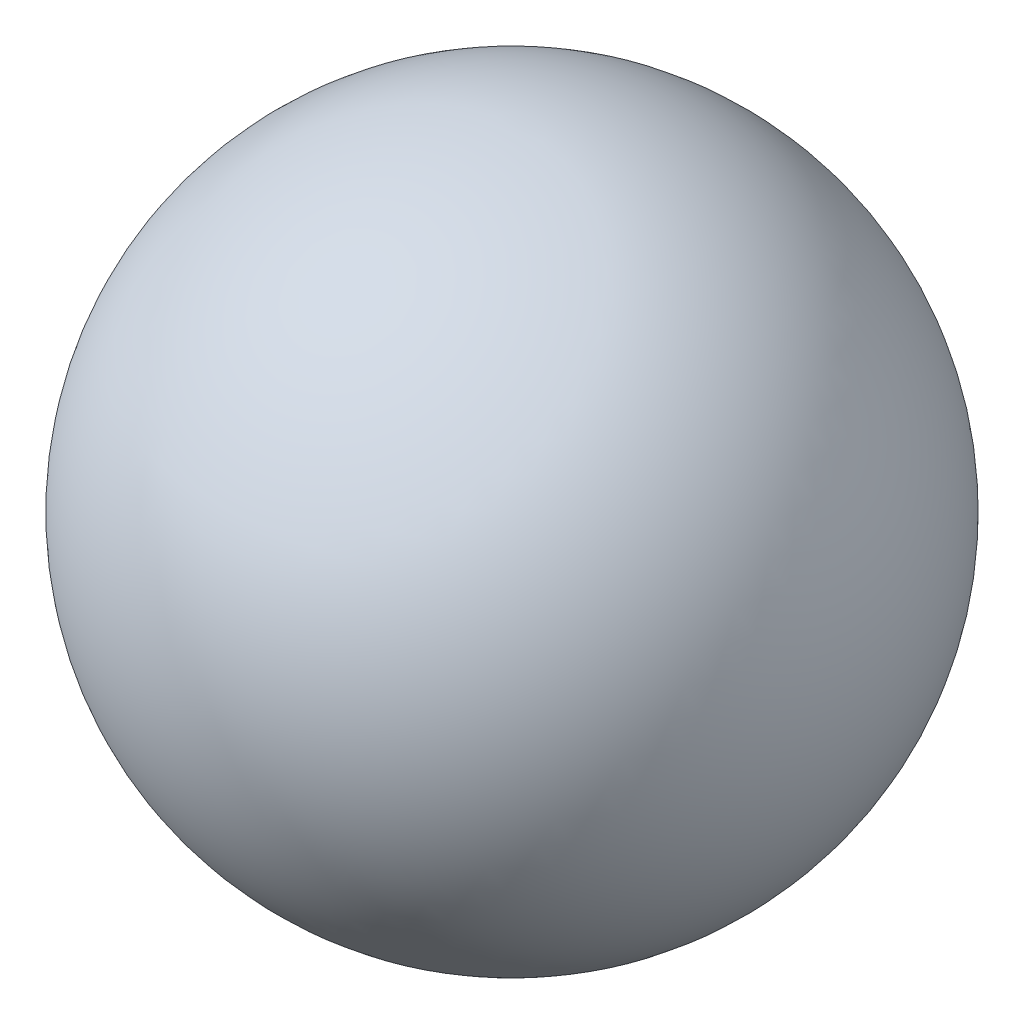
SolidWorks part; units mm, degrees
ref_plane "Front Plane" through (0, 0, 0) normal (0, 0, 1) x (1, 0, 0)
ref_plane "Top Plane" through (0, 0, 0) normal (0, 1, 0) x (1, 0, 0)
ref_plane "Right Plane" through (0, 0, 0) normal (1, 0, 0) x (0, 0, -1)
sketch "Sketch1" plane through (0, 0, 0) normal (0, 0, 1) x (1, 0, 0)
  line L0 (-1272.5132, -243.7844) -> (-1272.5132, 2156.2156)
  arc A0 (-1272.5132, -243.7844) -> (-1272.5132, 2156.2156) centre (-1272.5132, 956.2156) ccw
  dimension "D1" = 1200
revolve "Revolve1" add sketch "Sketch1" angle 360 about L0
